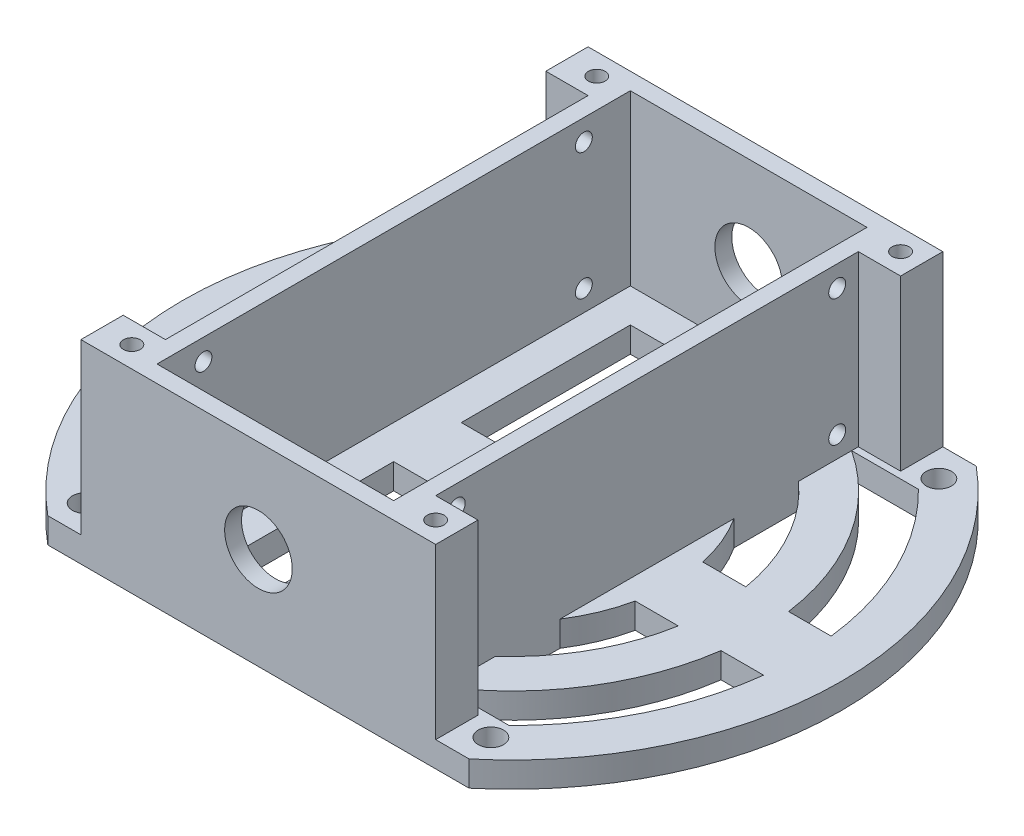
SolidWorks part; units mm, degrees
material "ABS"
ref_plane "Alzado" through (0, 0, 0) normal (0, 0, 1) x (1, 0, 0)
ref_plane "Planta" through (0, 0, 0) normal (0, 1, 0) x (1, 0, 0)
ref_plane "Vista lateral" through (0, 0, 0) normal (1, 0, 0) x (0, 0, -1)
sketch "Croquis2" plane through (0, 0, 0) normal (0, 1, 0) x (1, 0, 0)
  line L0 (-24.9199, 30) -> (24.9199, 30)
  line L1 (-24.9199, -30) -> (24.9199, -30)
  line L18 (-27.5, 27.6541) -> (-27.5, 17.3205) construction
  line L19 (0, 0) -> (0, 59.2338) construction
  line L20 (0, 0) -> (-70.768, 0) construction
  arc A0 (-24.9199, 30) -> (-24.9199, -30) centre (0, 0) ccw
  arc A9 (24.9199, -30) -> (24.9199, 30) centre (0, 0) ccw
  circle A10 centre (-24, 26.5) radius 1.5
  circle A11 centre (24, 26.5) radius 1.5
  circle A12 centre (-24, -26.5) radius 1.5
  circle A13 centre (24, -26.5) radius 1.5
  dimension "D1" = 3.5
  dimension "D3" = 3
  dimension "D2" = 3.5
extrude "Saliente-Extruir1" add sketch "Croquis2" along normal blind 3
sketch "Croquis3" plane through (0, 3, 0) normal (0, 1, 0) x (1, 0, 0)
  line L0 (0, 0) -> (0, -34.2383) construction
  line L1 (0, 0) -> (44.7743, 0) construction
  line L2 (-14, 0) -> (-14, 28)
  line L4 (14, 28) -> (14, -28)
  line L5 (14, -28) -> (-14, -28)
  line L6 (-14, -28) -> (-14, 0)
  line L7 (-14, 28) -> (0, 28)
  line L8 (0, 28) -> (14, 28)
  line L9 (-14, 28) -> (-16, 28)
  line L10 (-16, 28) -> (-16, -28)
  line L11 (-16, -28) -> (-14, -28)
  line L12 (14, 28) -> (15.97, 28)
  line L13 (15.97, 28) -> (15.97, -28)
  line L14 (15.97, -28) -> (14, -28)
  line L15 (-16, -28) -> (-14, -28)
  line L18 (24.9199, -31) -> (24.9199, 29) construction
  line L19 (-16, 28) -> (-16, 30)
  line L20 (24.9199, 30) -> (-24.9199, 30) construction
  line L21 (-16, 30) -> (15.97, 30)
  line L22 (15.97, 30) -> (15.97, 28)
  line L23 (-16, -28) -> (-16, -30)
  line L24 (-24.9199, -30) -> (24.9199, -30) construction
  line L25 (-16, -30) -> (15.97, -30)
  line L26 (15.97, -30) -> (15.97, -28)
  line M17 (-24.9199, -30) -> (24.9199, -30)
  line M19 (24.9199, 30) -> (-24.9199, 30)
  dimension "D1" = 28
  dimension "D2" = 28
  dimension "D3" = 14
  dimension "D4" = 14
  dimension "D6" = 8.9499
extrude "Saliente-Extruir2" add sketch "Croquis3" along normal blind 20 contours L10 L11 L6 L2 L9 | L14 L13 L12 L4 | L22 L19 L9 L7 L8 L12 M19 | L26 L14 L5 L11 L23 M17
sketch "Croquis4" plane through (15.97, 0, 0) normal (1, 0, 0) x (0, 0, -1)
  line L17 (30, 23) -> (25.0002, 23)
  line L18 (30, 23) -> (-30, 23) construction
  line L19 (25.0002, 23) -> (25.0002, 3)
  line L20 (25.0002, 3) -> (30, 3)
  line L22 (30, 3) -> (30, 23)
  line L25 (0, 0) -> (0, 32.1933) construction
  line L26 (-25.0002, 3) -> (-30, 3)
  line L27 (-30, 23) -> (-25.0002, 23)
  line L28 (-30, 3) -> (-30, 23)
  line L29 (-25.0002, 23) -> (-25.0002, 3)
extrude "Saliente-Extruir3" add sketch "Croquis4" along normal blind 5
sketch "Croquis5" plane through (-16, 0, 0) normal (-1, 0, 0) x (0, 0, 1)
  line L0 (-30, 23) -> (-25, 23)
  line L1 (-30, 23) -> (30, 23) construction
  line L2 (-30, 23) -> (-30, 3)
  line L3 (-30, 3) -> (-25, 3)
  line L4 (-30, 3) -> (30, 3) construction
  line L5 (-25, 3) -> (-25, 23)
  line L6 (0, 0) -> (0, 41.0061) construction
  line L7 (30, 3) -> (25, 3)
  line L8 (25, 3) -> (25, 23)
  line L9 (30, 23) -> (30, 3)
  line L10 (30, 23) -> (25, 23)
extrude "Saliente-Extruir4" add sketch "Croquis5" along normal blind 5
sketch "Croquis6" plane through (0, 23, 0) normal (0, 1, 0) x (1, 0, 0)
  line L2 (-21, -30) -> (20.97, -30) construction
  line L3 (20.97, -25.0002) -> (20.97, -30) construction
  line L4 (0, 0) -> (-38.9697, 0) construction
  line L5 (0.4979, 0) -> (0.4979, -36.2968) construction
  circle A0 centre (18.47, -27.5) radius 1
  circle A2 centre (18.47, 27.5) radius 1
  circle A3 centre (-17.4743, -27.5) radius 1
  circle A4 centre (-17.4743, 27.5) radius 1
  dimension "D1" = 2
  dimension "D4" = 2.5
  dimension "D5" = 2.5
extrude "Cortar-Extruir1" cut sketch "Croquis6" against normal blind 5
sketch "Croquis7" plane through (-16, 0, 0) normal (-1, 0, 0) x (0, 0, 1)
  line L0 (-25, 3) -> (-25, 23) construction
  line L2 (-25, 3) -> (25, 3) construction
  line L3 (0, 0) -> (0, 37.6305) construction
  circle A0 centre (-22.5, 5.5) radius 1
  circle A1 centre (22.5, 5.5) radius 1
  dimension "D1" = 2.5
  dimension "D2" = 2.5
extrude "Cortar-Extruir2" cut sketch "Croquis7" against normal through all
sketch "Croquis8" plane through (15.97, 0, 0) normal (1, 0, 0) x (0, 0, -1)
  line L0 (25.0002, 23) -> (-25.0002, 23) construction
  line L1 (25.0002, 23) -> (25.0002, 3) construction
  line L2 (0, 0) -> (0, 33.1591) construction
  circle A3 centre (22.5002, 20.5) radius 1
  circle A4 centre (-22.5002, 20.5) radius 1
  dimension "D1" = 2.5
  dimension "D3" = 2
  dimension "D2" = 2.5
extrude "Cortar-Extruir3" cut sketch "Croquis8" against normal through all
sketch "Croquis9" plane through (0, 3, 0) normal (0, 1, 0) x (1, 0, 0)
  line L0 (0, 0) -> (0, 45.656) construction
  line L1 (0, 0) -> (45.6061, 0) construction
  line L2 (15.97, 10.2936) -> (15.97, 17.9153)
  line L3 (15.97, 25.0002) -> (15.97, -25.0002) construction
  line L4 (15.97, -10.2936) -> (15.97, -17.9153)
  line L5 (15.97, 24.2066) -> (23.8755, 24.2066)
  line L6 (15.97, -24.2066) -> (23.8755, -24.2066)
  line L7 (-15.97, -10.2936) -> (-15.97, -17.9153)
  line L8 (-15.97, 10.2936) -> (-15.97, 17.9153)
  line L9 (-15.97, 24.2066) -> (-23.8755, 24.2066)
  line L10 (-15.97, -24.2066) -> (-23.8755, -24.2066)
  line L11 (-10, 4) -> (-10, 24)
  line L12 (-10, 24) -> (-4, 24)
  line L13 (-4, 24) -> (-4, 4)
  line L15 (10, 4) -> (4, 4)
  line L16 (4, 24) -> (4, 4)
  line L17 (-14, -28) -> (-14, 28) construction
  line L18 (10, 24) -> (4, 24)
  line L19 (14, 28) -> (-14, 28) construction
  line L20 (-10, 4) -> (-4, 4)
  line L21 (10, 4) -> (10, 24)
  line L22 (10, -4) -> (10, -24)
  line L23 (-10, -4) -> (-4, -4)
  line L24 (10, -24) -> (4, -24)
  line L25 (4, -24) -> (4, -4)
  line L26 (10, -4) -> (4, -4)
  line L27 (-4, -24) -> (-4, -4)
  line L28 (-10, -24) -> (-4, -24)
  line L29 (-10, -4) -> (-10, -24)
  line L30 (18.5742, 4) -> (23.6643, 4)
  line L31 (18.5742, -4) -> (23.6643, -4)
  line L32 (-18.5742, 4) -> (-23.6643, 4)
  line L33 (-18.5742, -4) -> (-23.6643, -4)
  line L34 (-28.7228, 4) -> (-33.7639, 4)
  line L35 (-28.7228, -4) -> (-33.7639, -4)
  line L36 (28.7228, 4) -> (33.7639, 4)
  line L37 (28.7228, -4) -> (33.7639, -4)
  arc A0 (23.8755, -24.2066) -> (33.7639, -4) centre (0, 0) ccw
  arc A1 (15.97, -24.2066) -> (28.7228, -4) centre (0, 0) ccw
  arc A2 (15.97, -17.9153) -> (23.6643, -4) centre (0, 0) ccw
  arc A3 (15.97, -10.2936) -> (18.5742, -4) centre (0, 0) ccw
  arc A4 (-15.97, 10.2936) -> (-18.5742, 4) centre (0, 0) ccw
  arc A5 (-15.97, 17.9153) -> (-23.6643, 4) centre (0, 0) ccw
  arc A6 (-23.8755, 24.2066) -> (-33.7639, 4) centre (0, 0) ccw
  arc A7 (-15.97, 24.2066) -> (-28.7228, 4) centre (0, 0) ccw
  arc A10 (-28.7228, -4) -> (-15.97, -24.2066) centre (0, 0) ccw
  arc A11 (-33.7639, -4) -> (-23.8755, -24.2066) centre (0, 0) ccw
  arc A12 (-23.6643, -4) -> (-15.97, -17.9153) centre (0, 0) ccw
  arc A13 (-18.5742, -4) -> (-15.97, -10.2936) centre (0, 0) ccw
  arc A14 (23.6643, 4) -> (15.97, 17.9153) centre (0, 0) ccw
  arc A15 (18.5742, 4) -> (15.97, 10.2936) centre (0, 0) ccw
  arc A16 (33.7639, 4) -> (23.8755, 24.2066) centre (0, 0) ccw
  arc A17 (28.7228, 4) -> (15.97, 24.2066) centre (0, 0) ccw
  dimension "D1" = 4
  dimension "D2" = 4
  dimension "D3" = 4
  dimension "D4" = 4
extrude "Cortar-Extruir5" cut sketch "Croquis9" against normal blind 10
sketch "Croquis10" plane through (0, 0, 30) normal (0, 0, 1) x (1, 0, 0)
  line L0 (0, 0) -> (0, 12)
  circle A0 centre (0, 12) radius 4
extrude "Cortar-Extruir6" cut sketch "Croquis10" against normal through all both and the other way through all
